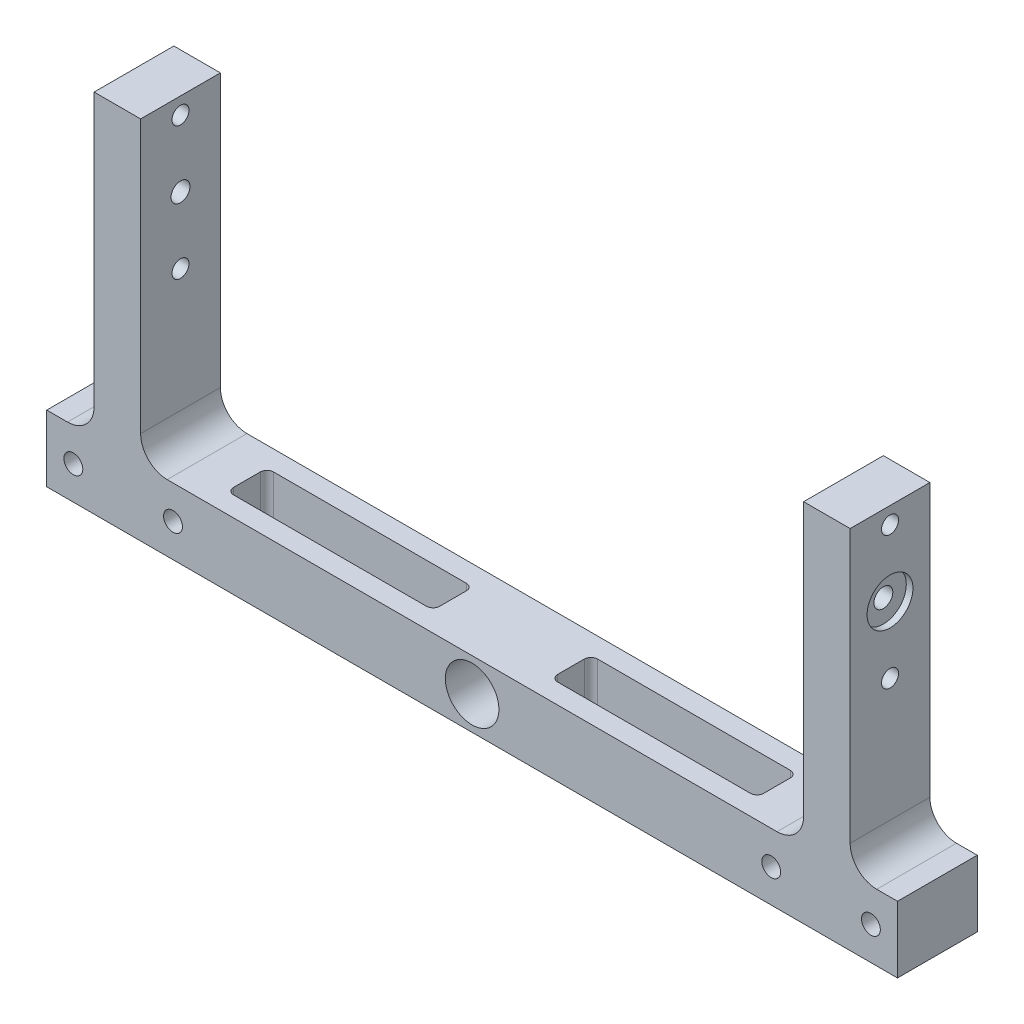
SolidWorks part; units mm, degrees
material "ABS"
ref_plane "Front Plane" through (0, 0, 0) normal (0, 0, 1) x (1, 0, 0)
ref_plane "Top Plane" through (0, 0, 0) normal (0, 1, 0) x (1, 0, 0)
ref_plane "Right Plane" through (0, 0, 0) normal (1, 0, 0) x (0, 0, -1)
sketch "Sketch1" plane through (0, 0, 0) normal (0, 0, 1) x (1, 0, 0)
  line L1 (-81.28, 6.35) -> (81.28, 6.35)
  line L2 (-81.28, 6.35) -> (-81.28, -6.35)
  line L3 (-81.28, -6.35) -> (81.28, -6.35)
  line L4 (81.28, 6.35) -> (81.28, -6.35)
  line L5 (-81.28, 6.35) -> (81.28, -6.35) construction
  line L6 (-81.28, -6.35) -> (81.28, 6.35) construction
  point P0 (0, 0)
  dimension "D1" = 12.7
  dimension "D2" = 162.56
extrude "Boss-Extrude1" add sketch "Sketch1" along normal blind 15.24 contours L1 L4 L3 L2
sketch "Sketch2" plane through (0, 0, 0) normal (0, 0, -1) x (-1, 0, 0)
  line L0 (-81.28, 6.35) -> (-81.28, -6.35) construction
  line L1 (81.28, -6.35) -> (-81.28, -6.35) construction
  circle A0 centre (-76.2, 0) radius 1.8034
  circle A1 centre (-57.15, 0) radius 1.8034
  circle A2 centre (57.15, 0) radius 1.8034
  circle A3 centre (76.2, 0) radius 1.8034
  dimension "D1" = 3.6068
  dimension "D2" = 3.6068
  dimension "D3" = 3.6068
  dimension "D4" = 3.6068
  dimension "D5" = 5.08
  dimension "D6" = 19.05
  dimension "D7" = 133.35
  dimension "D8" = 152.4
  dimension "D9" = 6.35
extrude "Cut-Extrude1" cut sketch "Sketch2" against normal blind 15.24
sketch "Sketch3" plane through (0, 0, 0) normal (0, 0, -1) x (-1, 0, 0)
  circle A0 centre (0, 0) radius 5.1181
  dimension "D1" = 10.2362
extrude "Cut-Extrude2" cut sketch "Sketch3" against normal blind 15.24
sketch "Sketch4" plane through (0, 6.35, 0) normal (0, 1, 0) x (1, 0, 0)
  line L0 (-81.28, -15.24) -> (81.28, -15.24) construction
  line L1 (72.23, -15.24) -> (63.34, -15.24)
  line L2 (72.23, -15.24) -> (72.23, 0)
  line L3 (72.23, 0) -> (63.34, 0)
  line L4 (63.34, -15.24) -> (63.34, 0)
  line L5 (-81.28, 0) -> (81.28, 0) construction
  line L6 (81.28, -15.24) -> (81.28, 0) construction
  line L7 (-63.3425, -15.24) -> (-72.2325, -15.24)
  line L8 (-63.3425, -15.24) -> (-63.3425, 0)
  line L9 (-63.3425, 0) -> (-72.2325, 0)
  line L10 (-72.2325, -15.24) -> (-72.2325, 0)
  dimension "D1" = 8.89
  dimension "D2" = 8.89
  dimension "D3" = 144.4625
  dimension "D4" = 9.05
extrude "Boss-Extrude2" add sketch "Sketch4" along normal blind 57.15
fillet "Fillet1" radius 5.08 4 edges at (-63.3425, 6.35, 7.62) (-72.2325, 6.35, 7.62) (63.34, 6.35, 7.62) (72.23, 6.35, 7.62)
sketch "Sketch5" plane through (72.23, 0, 0) normal (1, 0, 0) x (0, 0, -1)
  line L0 (-15.24, 63.5) -> (-15.24, 11.43) construction
  line L1 (-15.24, 63.5) -> (0, 63.5) construction
  circle A0 centre (-7.62, 60.325) radius 1.6256
  circle A2 centre (-7.62, 34.925) radius 1.6256
  circle A3 centre (-7.62, 47.625) radius 1.8034
  dimension "D1" = 3.2512
  dimension "D2" = 3.2512
  dimension "D6" = 3.6068
  dimension "D3" = 7.62
  dimension "D4" = 3.175
  dimension "D5" = 25.4
  dimension "D7" = 12.7
extrude "Cut-Extrude3" cut sketch "Sketch5" against normal blind 152.4 contours A2 | A3 | A0
sketch "Sketch6" plane through (72.23, 0, 0) normal (1, 0, 0) x (0, 0, -1)
  circle A0 centre (-7.62, 47.625) radius 4.3815
  dimension "D1" = 8.763
extrude "Cut-Extrude4" cut sketch "Sketch6" against normal blind 1.27
sketch "Sketch7" plane through (-72.2325, 0, 0) normal (-1, 0, 0) x (0, 0, 1)
  circle A0 centre (7.62, 47.625) radius 3.2639
  dimension "D1" = 6.5278
extrude "Cut-Extrude5" cut sketch "Sketch7" against normal blind 2.54
sketch "Sketch8" plane through (0, 6.35, 0) normal (0, 1, 0) x (1, 0, 0)
  line L0 (-58.2625, 0) -> (58.26, 0) construction
  line L1 (50.64, -11.43) -> (11.27, -11.43)
  line L2 (50.64, -11.43) -> (50.64, -3.81)
  line L3 (50.64, -3.81) -> (11.27, -3.81)
  line L4 (11.27, -11.43) -> (11.27, -3.81)
  line L5 (50.64, -11.43) -> (11.27, -3.81) construction
  line L6 (50.64, -3.81) -> (11.27, -11.43) construction
  line L7 (-11.2725, -3.81) -> (-50.6425, -3.81)
  line L8 (-11.2725, -3.81) -> (-11.2725, -11.43)
  line L9 (-11.2725, -11.43) -> (-50.6425, -11.43)
  line L10 (-50.6425, -3.81) -> (-50.6425, -11.43)
  line L11 (-11.2725, -3.81) -> (-50.6425, -11.43) construction
  line L12 (-11.2725, -11.43) -> (-50.6425, -3.81) construction
  line L13 (58.26, -15.24) -> (58.26, 0) construction
  line L14 (-58.2625, 0) -> (-58.2625, -15.24) construction
  point P0 (30.955, -7.62)
  point P5 (-30.9575, -7.62)
  dimension "D1" = 7.62
  dimension "D2" = 3.81
  dimension "D3" = 7.62
  dimension "D4" = 39.37
  dimension "D5" = 7.62
  dimension "D6" = 3.81
  dimension "D7" = 7.62
  dimension "D8" = 39.37
extrude "Cut-Extrude6" cut sketch "Sketch8" against normal blind 25.4
fillet "Fillet2" radius 1.27 4 edges at (11.27, 0, 3.81) (11.27, 0, 11.43) (50.64, 0, 11.43) (50.64, 0, 3.81)
fillet "Fillet3" radius 1.27 4 edges at (-50.6425, 0, 3.81) (-50.6425, 0, 11.43) (-11.2725, 0, 3.81) (-11.2725, 0, 11.43)
